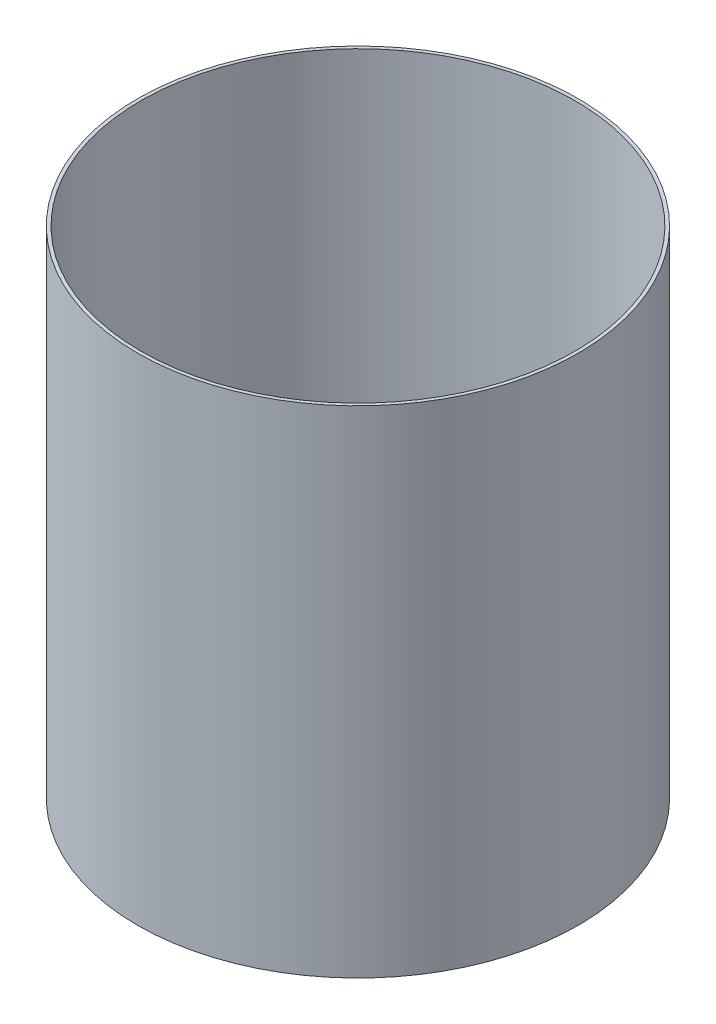
SolidWorks part; units mm, degrees
ref_plane "Front Plane" through (0, 0, 0) normal (0, 0, 1) x (1, 0, 0)
ref_plane "Top Plane" through (0, 0, 0) normal (0, 1, 0) x (1, 0, 0)
ref_plane "Right Plane" through (0, 0, 0) normal (1, 0, 0) x (0, 0, -1)
sketch "Sketch1" plane through (0, 0, 0) normal (0, 1, 0) x (1, 0, 0)
  circle A0 centre (0, 0) radius 66.7
  circle A1 centre (0, 0) radius 65.7
  dimension "D1" = 1
  dimension "D2" = 133.4
extrude "Boss-Extrude1" add sketch "Sketch1" along normal mid plane 150
